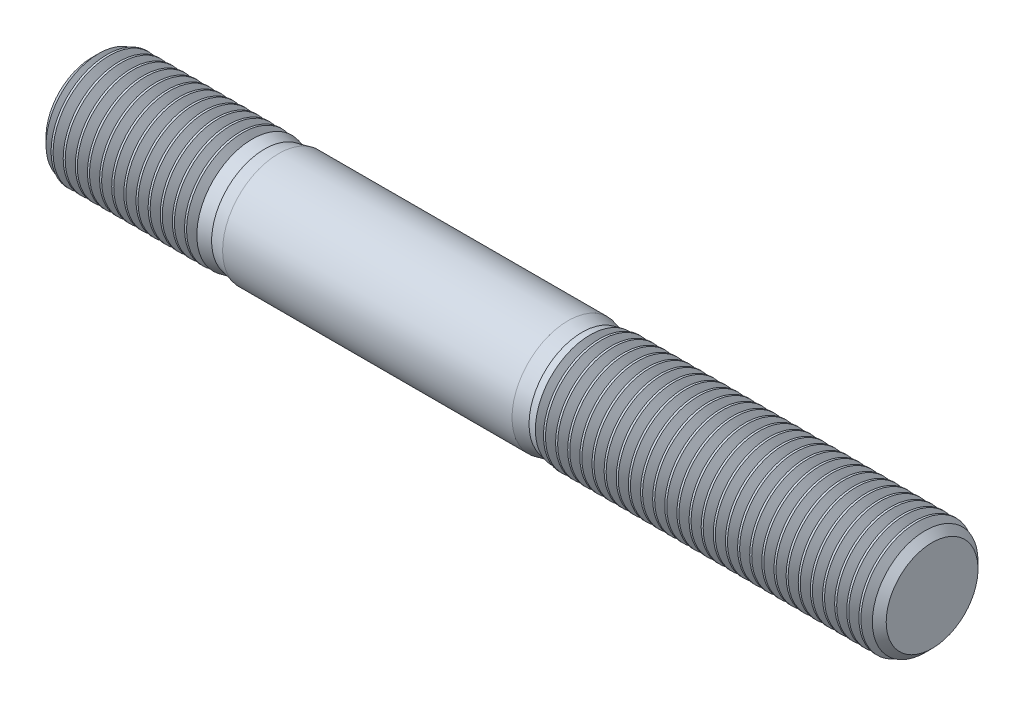
SolidWorks part; units mm, degrees
ref_plane "Front" through (0, 0, 0) normal (0, 0, 1) x (1, 0, 0)
ref_plane "Top" through (0, 0, 0) normal (0, 1, 0) x (1, 0, 0)
ref_plane "Right" through (0, 0, 0) normal (1, 0, 0) x (0, 0, -1)
sketch "Sketch1" plane through (0, 0, 0) normal (0, 0, 1) x (1, 0, 0)
  line L0 (-1.3108, 0) -> (30.3862, 0) construction
  line L1 (0, 0) -> (0, 3)
  line L2 (0, 3) -> (8.5, 3)
  line L3 (8.5, 3) -> (10, 2.675)
  line L4 (10, 2.675) -> (25.5, 2.675)
  line L5 (25.5, 2.675) -> (27, 3)
  line L6 (27, 3) -> (45, 3)
  line L7 (45, 3) -> (45, 0)
  line L8 (45, 0) -> (0, 0)
  dimension "X" = 1.5
  dimension "D2" = 1.5
  dimension "b" = 18
  dimension "d" = 6
  dimension "ds" = 5.35
  dimension "l" = 35
  dimension "bm" = 10
revolve "BaseHead" add sketch "Sketch1" angle 360 about L0
cosmetic thread "ThreadCosmetic1" parameters "D1"=8.5, "D2"=4.917
cosmetic thread "ThreadCosmetic2" parameters "b"=18, "D2"=4.917
chamfer "HeadChamfer" distance 0.5415 angle 45 2 edges at (0, 0, 3) (45, 0, 3)
sketch "Sketch2" plane through (0, 0, 0) normal (0, 0, 1) x (1, 0, 0)
  line L0 (-1.3108, 0) -> (31.2107, 0) construction
  line L2 (8.5, 2.675) -> (10, 3)
  line L3 (10, 3) -> (25.5, 3)
  line L4 (25.5, 3) -> (27, 2.675)
  line L7 (8.5, 3) -> (8.5, -3) construction
  line L9 (8.5, 2.675) -> (27, 2.675)
  line L10 (27, 3) -> (27, -3) construction
  dimension "D2" = 6
  dimension "D1" = 1.5
revolve "BaseBody" add sketch "Sketch2" angle 360 about L0
sketch "Sketch3" plane through (0, 0, 0) normal (0, 0, 1) x (1, 0, 0)
  line L0 (44.4585, 2.531) -> (44.7293, 3)
  line L1 (44.7293, 3) -> (44.7293, 3.5)
  line L2 (44.7293, 3.5) -> (44.1878, 3.5)
  line L3 (44.1878, 3.5) -> (44.1878, 3)
  line L4 (44.1878, 3) -> (44.4585, 2.531)
  line L5 (0, 0) -> (54.5942, 0) construction
  line L6 (44.4585, 3) -> (44.4585, -3) construction
  dimension "D1" = 60
  dimension "D2" = 60
  dimension "D3" = 0.5
  dimension "D4" = 0.5415
  dimension "D5" = 6
revolve "Cut-Revolve10" cut sketch "Sketch3" angle 360 about L5
pattern_linear "LPattern10" count 28 spacing 0.6498 along (-1, 0, 0) of "Cut-Revolve10"
sketch "Sketch4" plane through (0, 0, 0) normal (0, 0, 1) x (1, 0, 0)
  line L0 (0.5415, 2.531) -> (0.8122, 3)
  line L1 (0.8122, 3) -> (0.8122, 3.5)
  line L2 (0.8122, 3.5) -> (0.2707, 3.5)
  line L3 (0.2707, 3.5) -> (0.2707, 3)
  line L4 (0.2707, 3) -> (0.5415, 2.531)
  line L5 (0, 0) -> (16.1581, 0) construction
  line L6 (0, 2.4585) -> (0, -2.4585) construction
  line L7 (0.5415, 3) -> (0.5415, -3) construction
  dimension "D1" = 60
  dimension "D2" = 60
  dimension "D3" = 0.5
  dimension "D4" = 0.5415
  dimension "D5" = 6
revolve "Cut-Revolve11" cut sketch "Sketch4" angle 360 about L5
pattern_linear "LPattern11" count 13 spacing 0.6498 along (1, 0, 0) of "Cut-Revolve11"
equation "\"D2@Sketch1\" = \"X@Sketch1\""
equation "\"D2@ThreadCosmetic2\" = \"D2@ThreadCosmetic1\""
equation "\"D1@ThreadCosmetic1\" = \"bm@Sketch1\"-\"X@Sketch1\""
equation "\"b@ThreadCosmetic2\" = \"b@Sketch1\""
equation "\"D1@Sketch2\" = \"X@Sketch1\""
equation "\"D2@Sketch2\" = \"d@Sketch1\""
equation "\"D1@HeadChamfer\" =  ( \"d@Sketch1\" - \"D2@ThreadCosmetic1\" )  / 2"
equation "\"D5@Sketch3\" = \"d@Sketch1\""
equation "\"D4@Sketch3\" = (  \"d@Sketch1\" - \"D2@ThreadCosmetic2\" )  / 2"
equation "\"D3@LPattern10\" = \"D4@Sketch3\" * 1.2"
equation "\"D1@LPattern10\" = \"b@ThreadCosmetic2\" / \"D3@LPattern10\""
equation "\"D5@Sketch4\" = \"d@Sketch1\""
equation "\"D4@Sketch4\" = (  \"d@Sketch1\" - \"D2@ThreadCosmetic1\" )  / 2"
equation "\"D3@LPattern11\" = \"D4@Sketch4\" * 1.2"
equation "\"D1@LPattern11\" = \"D1@ThreadCosmetic1\" / \"D3@LPattern11\""
